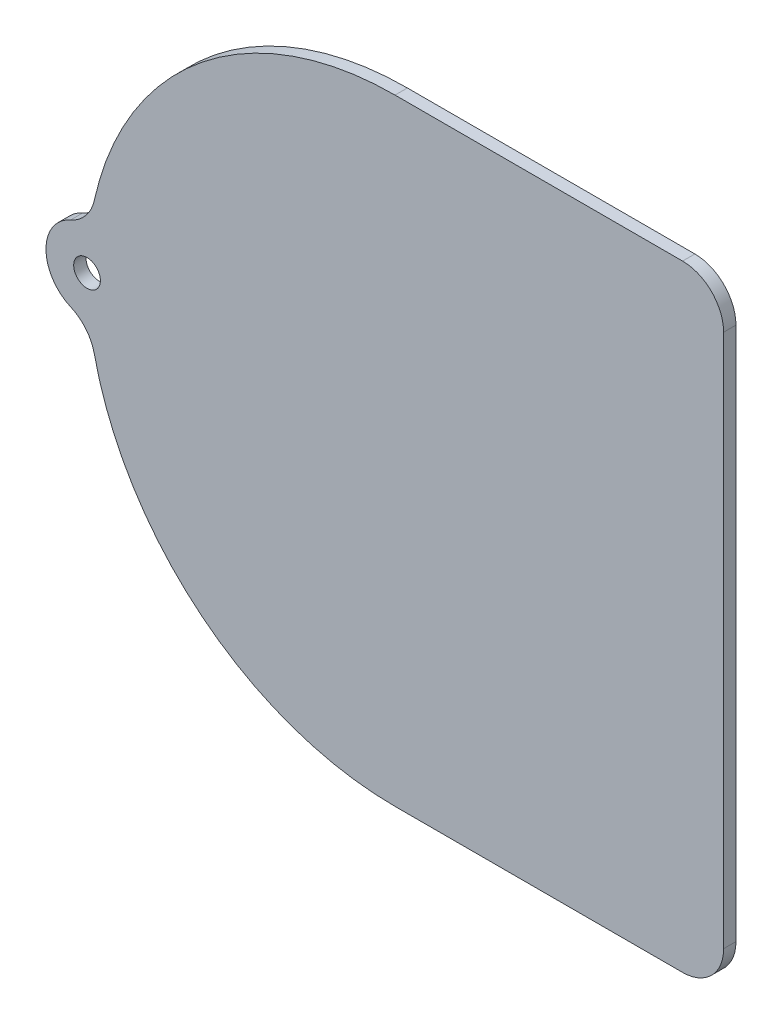
SolidWorks part; units mm, degrees
material "Acrylic (Medium-high impact)"
ref_plane "Front Plane" through (0, 0, 0) normal (0, 0, 1) x (1, 0, 0)
ref_plane "Top Plane" through (0, 0, 0) normal (0, 1, 0) x (1, 0, 0)
ref_plane "Right Plane" through (0, 0, 0) normal (1, 0, 0) x (0, 0, -1)
sketch "Sketch1" plane through (0, 0, 0) normal (0, 0, 1) x (1, 0, 0)
  line L0 (0, 75) -> (70, 75)
  line L1 (80, 65) -> (80, -65)
  line L2 (70, -75) -> (0, -75)
  arc A0 (0, 75) -> (-73.2353, 16.1738) centre (0, 0) ccw
  arc A1 (70, 75) -> (80, 65) centre (70, 65) cw
  arc A2 (80, -65) -> (70, -75) centre (70, -65) cw
  arc A3 (-79, 9.1652) -> (-79, -9.1652) centre (-75, 0) ccw
  arc A4 (-79, 9.1652) -> (-73.2353, 16.1738) centre (-83, 18.3303) ccw
  arc A5 (-73.2353, -16.1738) -> (-79, -9.1652) centre (-83, -18.3303) ccw
  arc A6 (-73.2353, -16.1738) -> (0, -75) centre (0, 0) ccw
  circle A7 centre (-75, 0) radius 3.25
  dimension "D1" = 10
  dimension "D2" = 75
  dimension "D3" = 5
  dimension "D4" = 20
  dimension "D5" = 6.5
extrude "Main Plate" add sketch "Sketch1" along normal blind 3
